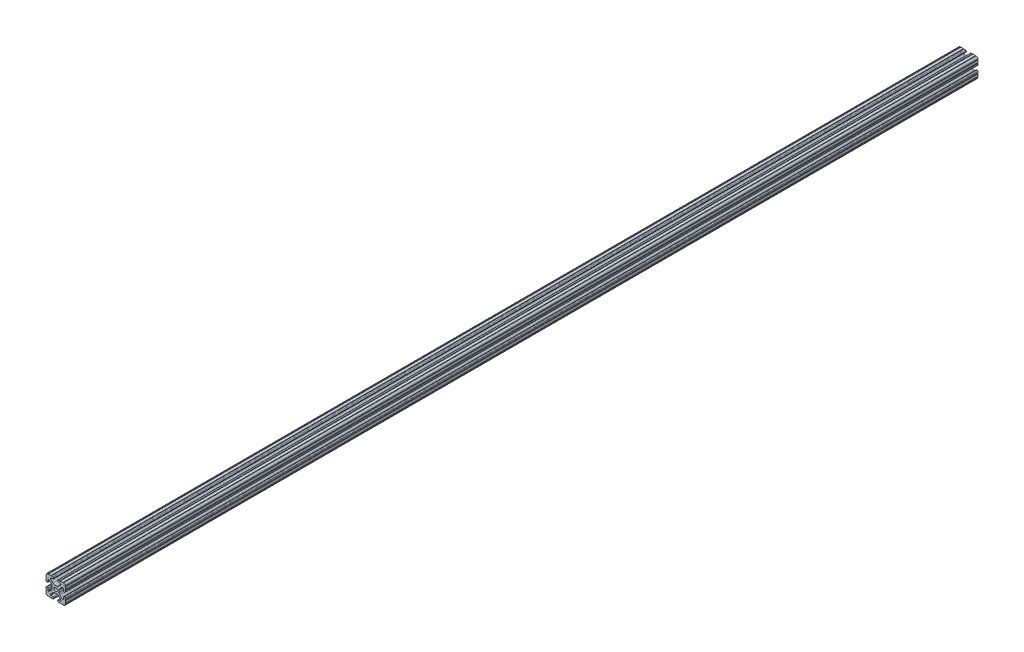
SolidWorks part; units mm, degrees
material "6061 Alloy"
ref_plane "Front Plane" through (0, 0, 0) normal (0, 0, 1) x (1, 0, 0)
ref_plane "Top Plane" through (0, 0, 0) normal (0, 1, 0) x (1, 0, 0)
ref_plane "Right Plane" through (0, 0, 0) normal (1, 0, 0) x (0, 0, -1)
sketch "Sketch1" plane through (0, 0, 0) normal (0, 0, 1) x (1, 0, 0)
  line L0 (0, 25.6181) -> (0, -24.623) construction
  line L1 (-20.8943, 0) -> (20.4607, 0) construction
  line L2 (-10.0229, 12.9148) -> (-5.2522, 8.144)
  line L3 (-10.287, 14.0843) -> (-10.287, 13.5524)
  line L4 (-5.6176, 14.986) -> (-9.3853, 14.986)
  line L5 (-4.064, 17.4964) -> (-4.064, 16.5396)
  line L6 (-7.9742, 19.05) -> (-5.6176, 19.05)
  line L7 (-14.3277, 19.05) -> (-9.4982, 19.05)
  line L8 (-19.05, 9.4961) -> (-19.05, 14.3277)
  line L9 (-19.05, 5.6176) -> (-19.05, 7.9763)
  line L10 (-16.5396, 4.064) -> (-17.4964, 4.064)
  line L11 (-14.986, 9.3853) -> (-14.986, 5.6176)
  line L12 (-13.516, 10.287) -> (-14.0843, 10.287)
  line L13 (-8.1476, 5.2921) -> (-12.8784, 10.0229)
  line L14 (-6.7564, -1.9335) -> (-6.7564, 1.9335)
  line L15 (-12.8784, -10.0229) -> (-8.1476, -5.2921)
  line L16 (-14.0843, -10.287) -> (-13.516, -10.287)
  line L17 (-14.986, -5.6176) -> (-14.986, -9.3853)
  line L18 (-17.4964, -4.064) -> (-16.5396, -4.064)
  line L19 (-19.05, -7.9763) -> (-19.05, -5.6176)
  line L20 (-19.05, -14.3277) -> (-19.05, -9.4961)
  line L21 (-9.4961, -19.05) -> (-14.3277, -19.05)
  line L22 (-5.6176, -19.05) -> (-7.9763, -19.05)
  line L23 (-4.064, -17.4964) -> (-4.064, -16.5396)
  line L24 (10.0229, -12.9148) -> (5.2522, -8.144)
  line L25 (10.287, -14.0843) -> (10.287, -13.5524)
  line L26 (5.6176, -14.986) -> (9.3853, -14.986)
  line L28 (-1.9022, 6.7564) -> (1.9022, 6.7564)
  line L29 (-1.9022, -6.7564) -> (1.9022, -6.7564)
  line L31 (-5.6176, -14.986) -> (-9.3853, -14.986)
  line L32 (-10.287, -14.0843) -> (-10.287, -13.5524)
  line L33 (-10.0229, -12.9148) -> (-5.2522, -8.144)
  line L66 (4.064, -16.5396) -> (4.064, -17.4964)
  line L67 (5.6176, -19.05) -> (7.9763, -19.05)
  line L68 (9.4961, -19.05) -> (14.3277, -19.05)
  line L69 (19.05, -14.3277) -> (19.05, -9.4961)
  line L70 (19.05, -7.9763) -> (19.05, -5.6176)
  line L71 (17.4964, -4.064) -> (16.5396, -4.064)
  line L72 (14.986, -5.6176) -> (14.986, -9.3853)
  line L73 (14.0843, -10.287) -> (13.516, -10.287)
  line L74 (12.8784, -10.0229) -> (8.1476, -5.2921)
  line L75 (6.7564, -1.9335) -> (6.7564, 1.9335)
  line L76 (8.1476, 5.2921) -> (12.8784, 10.0229)
  line L77 (13.516, 10.287) -> (14.0843, 10.287)
  line L78 (14.986, 9.3853) -> (14.986, 5.6176)
  line L79 (16.5396, 4.064) -> (17.4964, 4.064)
  line L80 (19.05, 5.6176) -> (19.05, 7.9763)
  line L81 (19.05, 9.4961) -> (19.05, 14.3277)
  line L82 (14.3277, 19.05) -> (9.4982, 19.05)
  line L83 (7.9742, 19.05) -> (5.6176, 19.05)
  line L84 (4.064, 17.4964) -> (4.064, 16.5396)
  line L85 (5.6176, 14.986) -> (9.3853, 14.986)
  line L86 (10.287, 14.0843) -> (10.287, 13.5524)
  line L87 (10.0229, 12.9148) -> (5.2522, 8.144)
  arc A0 (-10.0229, 12.9148) -> (-10.287, 13.5524) centre (-9.3853, 13.5524) cw
  circle A1 centre (0, 0) radius 3.3274
  arc A2 (-10.287, 14.0843) -> (-9.3853, 14.986) centre (-9.3853, 14.0843) cw
  arc A3 (-4.064, 16.5396) -> (-5.6176, 14.986) centre (-5.6176, 16.5396) cw
  arc A4 (-5.6176, 19.05) -> (-4.064, 17.4964) centre (-5.6176, 17.4964) cw
  arc A5 (-7.9742, 19.05) -> (-9.4982, 19.05) centre (-8.7362, 19.05) cw
  arc A6 (-14.3277, 19.05) -> (-15.8475, 19.05) centre (-15.0876, 18.9933) cw
  arc A7 (-19.05, 15.8475) -> (-15.8475, 19.05) centre (-15.8751, 15.8751) cw
  arc A8 (-19.05, 15.8475) -> (-19.05, 14.3277) centre (-18.9933, 15.0876) cw
  arc A9 (-19.05, 9.4961) -> (-19.05, 7.9763) centre (-18.9933, 8.7362) cw
  arc A10 (-17.4964, 4.064) -> (-19.05, 5.6176) centre (-17.4964, 5.6176) cw
  arc A11 (-14.986, 5.6176) -> (-16.5396, 4.064) centre (-16.5396, 5.6176) cw
  arc A12 (-14.986, 9.3853) -> (-14.0843, 10.287) centre (-14.0843, 9.3853) cw
  arc A13 (-13.516, 10.287) -> (-12.8784, 10.0229) centre (-13.516, 9.3853) cw
  arc A14 (-8.1476, 5.2921) -> (-6.7564, 1.9335) centre (-11.5062, 1.9335) cw
  arc A15 (-6.7564, -1.9335) -> (-8.1476, -5.2921) centre (-11.5062, -1.9335) cw
  arc A16 (-12.8784, -10.0229) -> (-13.516, -10.287) centre (-13.516, -9.3853) cw
  arc A17 (-14.0843, -10.287) -> (-14.986, -9.3853) centre (-14.0843, -9.3853) cw
  arc A18 (-16.5396, -4.064) -> (-14.986, -5.6176) centre (-16.5396, -5.6176) cw
  arc A19 (-19.05, -5.6176) -> (-17.4964, -4.064) centre (-17.4964, -5.6176) cw
  arc A20 (-19.05, -7.9763) -> (-19.05, -9.4961) centre (-18.9933, -8.7362) cw
  arc A21 (-19.05, -14.3277) -> (-19.05, -15.8475) centre (-18.9933, -15.0876) cw
  arc A22 (-15.8475, -19.05) -> (-19.05, -15.8475) centre (-15.8751, -15.8751) cw
  arc A23 (-15.8475, -19.05) -> (-14.3277, -19.05) centre (-15.0876, -18.9933) cw
  arc A24 (-9.4961, -19.05) -> (-7.9763, -19.05) centre (-8.7362, -18.9933) cw
  arc A25 (-4.064, -17.4964) -> (-5.6176, -19.05) centre (-5.6176, -17.4964) cw
  arc A26 (-5.2522, -8.144) -> (-1.9022, -6.7564) centre (-1.9022, -11.494) cw
  arc A27 (1.9022, -6.7564) -> (5.2522, -8.144) centre (1.9022, -11.494) cw
  arc A28 (10.0229, -12.9148) -> (10.287, -13.5524) centre (9.3853, -13.5524) cw
  arc A29 (10.287, -14.0843) -> (9.3853, -14.986) centre (9.3853, -14.0843) cw
  arc A30 (4.064, -16.5396) -> (5.6176, -14.986) centre (5.6176, -16.5396) cw
  arc A31 (-4.064, -16.5396) -> (-5.6176, -14.986) centre (-5.6176, -16.5396) ccw
  arc A32 (-10.287, -14.0843) -> (-9.3853, -14.986) centre (-9.3853, -14.0843) ccw
  arc A33 (-10.0229, -12.9148) -> (-10.287, -13.5524) centre (-9.3853, -13.5524) ccw
  arc A79 (4.064, -17.4964) -> (5.6176, -19.05) centre (5.6176, -17.4964) ccw
  arc A80 (9.4961, -19.05) -> (7.9763, -19.05) centre (8.7362, -18.9933) ccw
  arc A81 (15.8475, -19.05) -> (14.3277, -19.05) centre (15.0876, -18.9933) ccw
  arc A82 (15.8475, -19.05) -> (19.05, -15.8475) centre (15.8751, -15.8751) ccw
  arc A83 (19.05, -14.3277) -> (19.05, -15.8475) centre (18.9933, -15.0876) ccw
  arc A84 (19.05, -7.9763) -> (19.05, -9.4961) centre (18.9933, -8.7362) ccw
  arc A85 (19.05, -5.6176) -> (17.4964, -4.064) centre (17.4964, -5.6176) ccw
  arc A86 (16.5396, -4.064) -> (14.986, -5.6176) centre (16.5396, -5.6176) ccw
  arc A87 (14.0843, -10.287) -> (14.986, -9.3853) centre (14.0843, -9.3853) ccw
  arc A88 (12.8784, -10.0229) -> (13.516, -10.287) centre (13.516, -9.3853) ccw
  arc A89 (6.7564, -1.9335) -> (8.1476, -5.2921) centre (11.5062, -1.9335) ccw
  arc A90 (8.1476, 5.2921) -> (6.7564, 1.9335) centre (11.5062, 1.9335) ccw
  arc A91 (13.516, 10.287) -> (12.8784, 10.0229) centre (13.516, 9.3853) ccw
  arc A92 (14.986, 9.3853) -> (14.0843, 10.287) centre (14.0843, 9.3853) ccw
  arc A93 (14.986, 5.6176) -> (16.5396, 4.064) centre (16.5396, 5.6176) ccw
  arc A94 (17.4964, 4.064) -> (19.05, 5.6176) centre (17.4964, 5.6176) ccw
  arc A95 (19.05, 9.4961) -> (19.05, 7.9763) centre (18.9933, 8.7362) ccw
  arc A96 (19.05, 15.8475) -> (19.05, 14.3277) centre (18.9933, 15.0876) ccw
  arc A97 (19.05, 15.8475) -> (15.8475, 19.05) centre (15.8751, 15.8751) ccw
  arc A98 (14.3277, 19.05) -> (15.8475, 19.05) centre (15.0876, 18.9933) ccw
  arc A99 (7.9742, 19.05) -> (9.4982, 19.05) centre (8.7362, 19.05) ccw
  arc A100 (5.6176, 19.05) -> (4.064, 17.4964) centre (5.6176, 17.4964) ccw
  arc A101 (4.064, 16.5396) -> (5.6176, 14.986) centre (5.6176, 16.5396) ccw
  arc A102 (10.287, 14.0843) -> (9.3853, 14.986) centre (9.3853, 14.0843) ccw
  arc A103 (10.0229, 12.9148) -> (10.287, 13.5524) centre (9.3853, 13.5524) ccw
  arc A104 (1.9022, 6.7564) -> (5.2522, 8.144) centre (1.9022, 11.494) ccw
  arc A105 (-5.2522, 8.144) -> (-1.9022, 6.7564) centre (-1.9022, 11.494) ccw
  dimension "D1" = 6.6548
  dimension "D2" = 19.05
  dimension "D3" = 38.1
  dimension "D4" = 20.574
  dimension "D5" = 13.5128
  dimension "D6" = 4.064
  dimension "D7" = 8.128
  dimension "D8" = 4.064
  dimension "D9" = 12.2936
extrude "Extrude1" add sketch "Sketch1" against normal blind 1800
